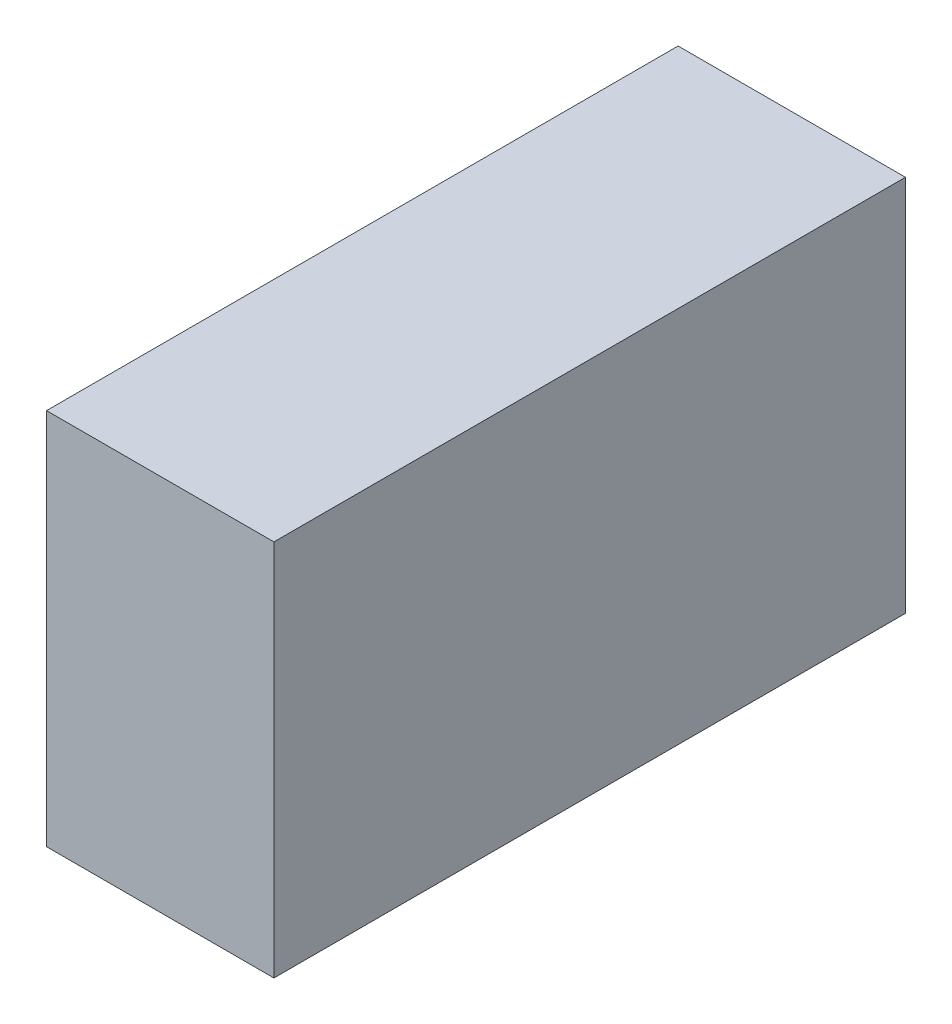
SolidWorks part; units mm, degrees
ref_plane "Front Plane" through (0, 0, 0) normal (0, 0, 1) x (1, 0, 0)
ref_plane "Top Plane" through (0, 0, 0) normal (0, 1, 0) x (1, 0, 0)
ref_plane "Right Plane" through (0, 0, 0) normal (1, 0, 0) x (0, 0, -1)
sketch "Sketch1" plane through (0, 0, 0) normal (0, 1, 0) x (1, 0, 0)
  line L1 (-6.9492, 4.0254) -> (2.0508, 4.0254)
  line L2 (-6.9492, 4.0254) -> (-6.9492, -20.9746)
  line L3 (-6.9492, -20.9746) -> (2.0508, -20.9746)
  line L4 (2.0508, 4.0254) -> (2.0508, -20.9746)
  dimension "D1" = 9
  dimension "D2" = 25
extrude "Boss-Extrude1" add sketch "Sketch1" along normal blind 14.9505
